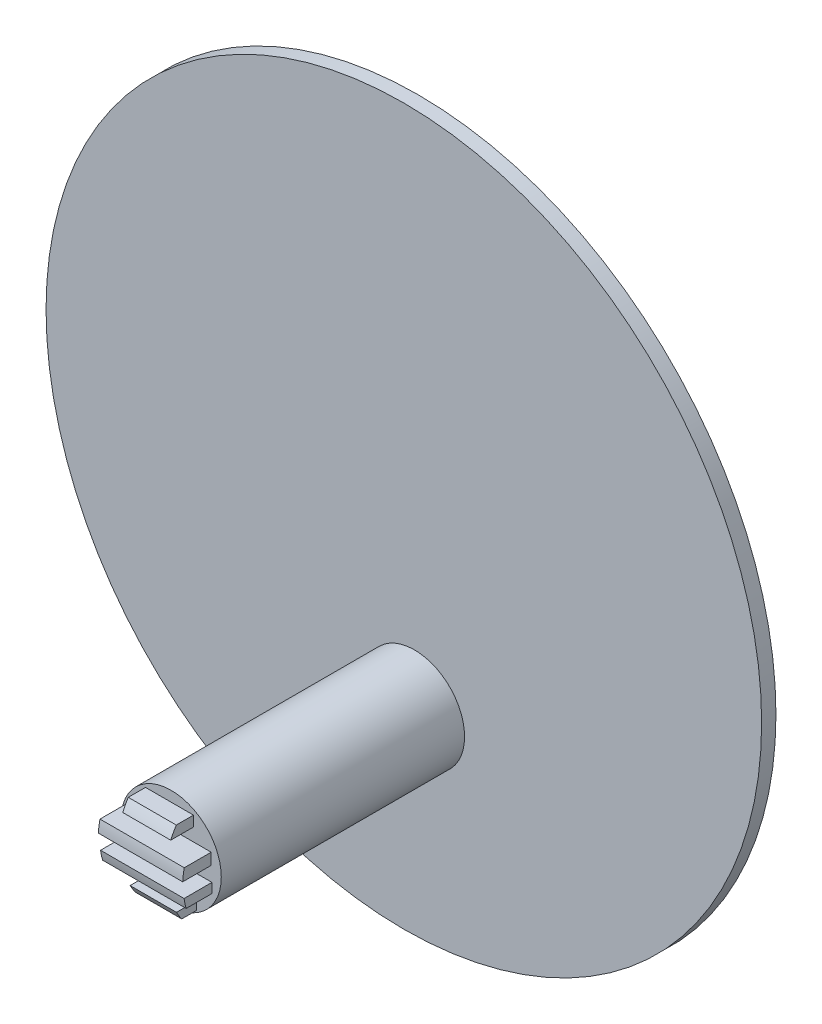
SolidWorks part; units mm, degrees
ref_plane "Front Plane" through (0, 0, 0) normal (0, 0, 1) x (1, 0, 0)
ref_plane "Top Plane" through (0, 0, 0) normal (0, 1, 0) x (1, 0, 0)
ref_plane "Right Plane" through (0, 0, 0) normal (1, 0, 0) x (0, 0, -1)
sketch "Sketch1" plane through (0, 0, 0) normal (0, 0, 1) x (1, 0, 0)
  circle A0 centre (-6.1844, 0) radius 10
  dimension "D1" = 20
extrude "Boss-Extrude1" add sketch "Sketch1" along normal blind 0.4
sketch "Sketch2" plane through (0, 0, 0.4) normal (0, 0, 1) x (1, 0, 0)
  circle A0 centre (-5.8869, -4.4881) radius 1.4
  dimension "D1" = 2.8
extrude "Boss-Extrude2" add sketch "Sketch2" along normal blind 6.8
sketch "Sketch5" plane through (0, 0, 7.2) normal (0, 0, 1) x (1, 0, 0)
  line L1 (-6.474, -5.6393) -> (-5.1772, -5.6393)
  line L2 (-6.474, -5.6393) -> (-6.474, -5.405)
  line L3 (-6.474, -5.405) -> (-5.1772, -5.405)
  line L4 (-5.1772, -5.6393) -> (-5.1772, -5.405)
extrude "Boss-Extrude4" add sketch "Sketch5" along normal up to surface (0.4142 mm away) separate body
sketch "Sketch6" plane through (0, 0, 7.2) normal (0, 0, 1) x (1, 0, 0)
  line L1 (-7.0819, -5.0165) -> (-4.7474, -5.0165)
  line L2 (-7.0819, -5.0165) -> (-7.0819, -4.7462)
  line L3 (-7.0819, -4.7462) -> (-4.7474, -4.7462)
  line L4 (-4.7474, -5.0165) -> (-4.7474, -4.7462)
extrude "Boss-Extrude5" add sketch "Sketch6" along normal up to surface (0.7205 mm away)
sketch "Sketch7" plane through (0, 0, 7.2) normal (0, 0, 1) x (1, 0, 0)
  line L1 (-7.1245, -4.3448) -> (-4.7686, -4.3448)
  line L2 (-7.1245, -4.3448) -> (-7.1245, -4.0262)
  line L3 (-7.1245, -4.0262) -> (-4.7686, -4.0262)
  line L4 (-4.7686, -4.3448) -> (-4.7686, -4.0262)
extrude "Boss-Extrude6" add sketch "Sketch7" along normal up to surface (0.7968 mm away)
sketch "Sketch8" plane through (0, 0, 7.2) normal (0, 0, 1) x (1, 0, 0)
  line L1 (-6.605, -3.6651) -> (-5.2636, -3.6651)
  line L2 (-6.605, -3.6651) -> (-6.605, -3.3759)
  line L3 (-6.605, -3.3759) -> (-5.2636, -3.3759)
  line L4 (-5.2636, -3.6651) -> (-5.2636, -3.3759)
extrude "Boss-Extrude7" add sketch "Sketch8" along normal up to surface (0.6359 mm away)
